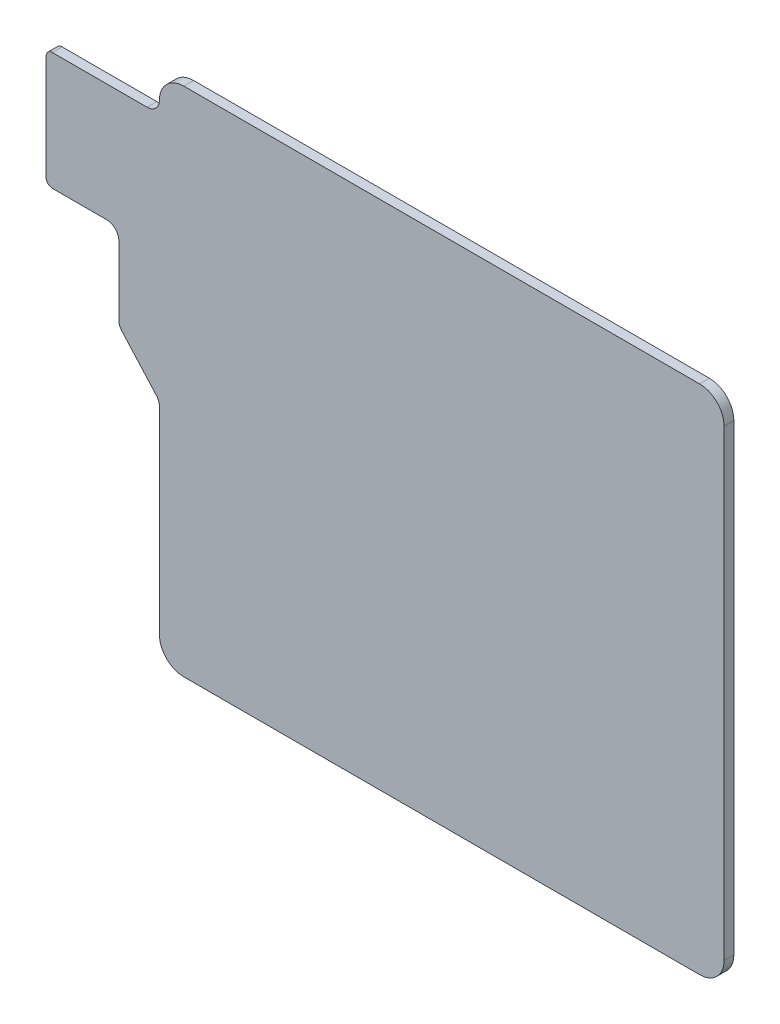
SolidWorks part; units mm, degrees
ref_plane "Front Plane" through (0, 0, 0) normal (0, 0, 1) x (1, 0, 0)
ref_plane "Top Plane" through (0, 0, 0) normal (0, 1, 0) x (1, 0, 0)
ref_plane "Right Plane" through (0, 0, 0) normal (1, 0, 0) x (0, 0, -1)
sketch "Sketch1" plane through (0, 0, 0) normal (0, 0, 1) x (1, 0, 0)
  line L0 (21.9069, -3.4061) -> (106.3629, -3.4061)
  line L1 (110.3629, 0.5939) -> (110.3629, 76.3639)
  line L2 (106.3629, 80.3639) -> (21.9068, 80.3639)
  line L3 (17.9069, 0.5939) -> (17.9069, 32.9411)
  line L4 (15.9068, 74.3639) -> (0.3648, 74.3639)
  line L5 (17.3309, 34.3454) -> (11.7795, 40.5326)
  line L6 (11.2681, 41.8683) -> (11.2681, 53.1025)
  line L7 (9.2681, 55.1025) -> (0.3663, 55.1025)
  line L8 (-0.6352, 73.3639) -> (-0.6337, 56.1025)
  arc A0 (106.3629, -3.4061) -> (110.3629, 0.5939) centre (106.3629, 0.5939) ccw
  arc A1 (110.3629, 76.3639) -> (106.3629, 80.3639) centre (106.3629, 76.3639) ccw
  arc A2 (21.9068, 80.3639) -> (17.9068, 76.3639) centre (21.9068, 76.3639) ccw
  arc A3 (21.9069, -3.4061) -> (17.9069, 0.5939) centre (21.9069, 0.5939) cw
  arc A4 (17.9068, 76.3639) -> (15.9068, 74.3639) centre (15.9068, 76.3639) cw
  arc A5 (0.3648, 74.3639) -> (-0.6352, 73.3639) centre (0.3648, 73.3639) ccw
  arc A6 (17.9069, 32.9411) -> (17.3309, 34.3454) centre (15.9068, 32.9411) ccw
  arc A7 (11.7795, 40.5326) -> (11.2681, 41.8683) centre (13.2681, 41.8683) cw
  arc A8 (11.2681, 53.1025) -> (9.2681, 55.1025) centre (9.2681, 53.1025) ccw
  arc A9 (0.3663, 55.1025) -> (-0.6337, 56.1025) centre (0.3663, 56.1025) cw
  point P34 (0, 0)
  dimension "D2" = 75.77
  dimension "D3" = 84.4561
  dimension "D5" = 4
  dimension "D6" = 4
  dimension "D7" = 4
  dimension "D8" = 4
  dimension "D9" = 2
  dimension "D11" = 1
  dimension "D12" = 2.0001
  dimension "D15" = 2
  dimension "D18" = 2
  dimension "D20" = 1
  dimension "D1" = 84.456
  dimension "D4" = 32.3472
  dimension "D10" = 15.542
  dimension "D13" = 44.6
  dimension "D14" = 8.3126
  dimension "D16" = 41.9
  dimension "D17" = 11.2342
  dimension "D19" = 8.9018
extrude "Boss-Extrude6" add sketch "Sketch1" along normal blind 1.6
